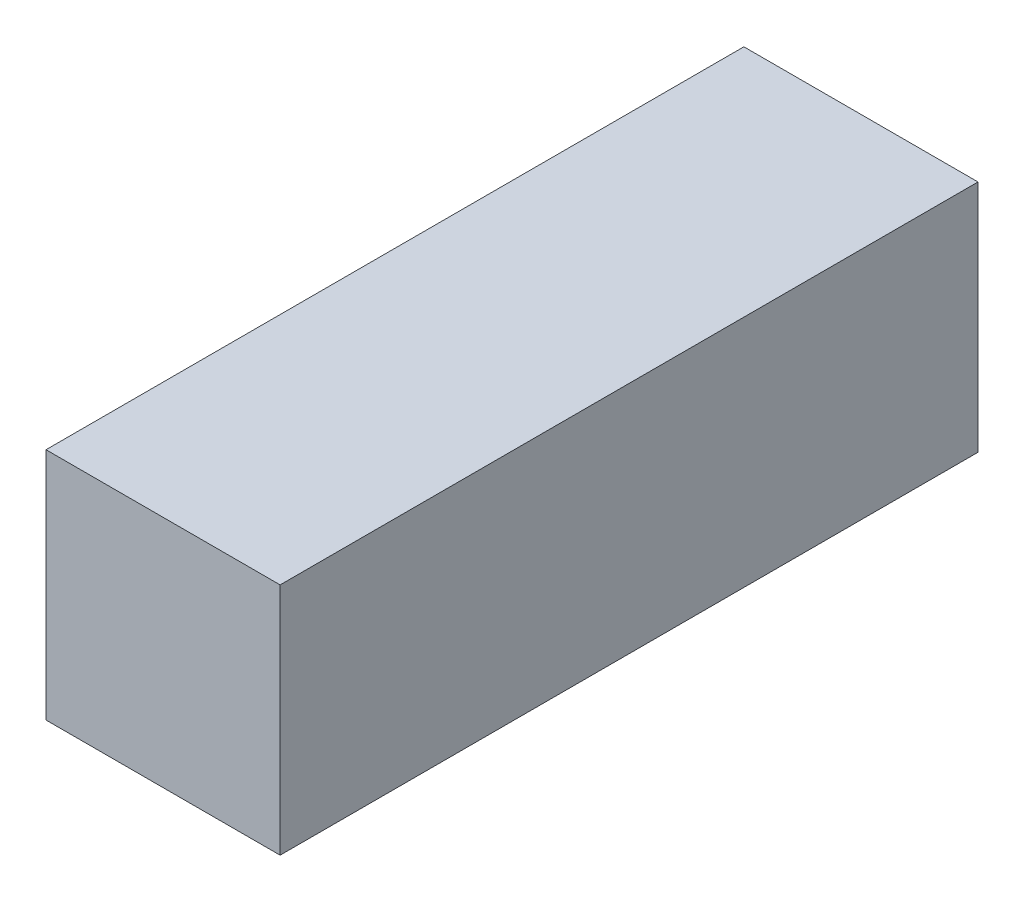
SolidWorks part; units mm, degrees
ref_plane "Front Plane" through (0, 0, 0) normal (0, 0, 1) x (1, 0, 0)
ref_plane "Top Plane" through (0, 0, 0) normal (0, 1, 0) x (1, 0, 0)
ref_plane "Right Plane" through (0, 0, 0) normal (1, 0, 0) x (0, 0, -1)
sketch "Sketch1" plane through (0, 0, 0) normal (0, 0, 1) x (1, 0, 0)
  line L0 (-1333.5, 2628.9) -> (-1333.5, -38.1)
  line L1 (-1295.4, 2590.8) -> (1295.4, 2590.8)
  line L2 (-1295.4, 2590.8) -> (-1295.4, 0)
  line L3 (-1295.4, 0) -> (1295.4, 0)
  line L4 (1295.4, 2590.8) -> (1295.4, 0)
  line L5 (-1295.4, 2590.8) -> (1295.4, 0) construction
  line L6 (-1295.4, 0) -> (1295.4, 2590.8) construction
  line L7 (-1333.5, -38.1) -> (1333.5, -38.1)
  line L8 (1333.5, 2628.9) -> (1333.5, -38.1)
  line L9 (-1333.5, 2628.9) -> (1333.5, 2628.9)
  point P0 (0, 1295.4)
  dimension "D1" = 2590.8
  dimension "D2" = 2590.8
  dimension "D3" = 38.1
extrude "Boss-Extrude1" add sketch "Sketch1" along normal blind 7924.8
sketch "Sketch2" plane through (0, 0, 7924.8) normal (0, 0, 1) x (1, 0, 0)
  line L0 (-1333.5, -38.1) -> (1333.5, -38.1) construction
  line L1 (1333.5, -38.1) -> (1333.5, 2628.9) construction
  line L2 (1333.5, 2628.9) -> (-1333.5, 2628.9) construction
  line L3 (-1333.5, 2628.9) -> (-1333.5, -38.1) construction
  line L4 (-1333.5, -38.1) -> (1333.5, -38.1)
  line L5 (1333.5, -38.1) -> (1333.5, 2628.9)
  line L6 (1333.5, 2628.9) -> (-1333.5, 2628.9)
  line L7 (-1333.5, 2628.9) -> (-1333.5, -38.1)
extrude "Boss-Extrude2" add sketch "Sketch2" along normal blind 25.4
sketch "Sketch3" plane through (0, 0, 7924.8) normal (0, 0, -1) x (-1, 0, 0)
  line L1 (-1295.4, 0) -> (-1155.7, 0)
  line L2 (-1295.4, 0) -> (-1295.4, 88.9)
  line L3 (-1295.4, 88.9) -> (-1155.7, 88.9)
  line L4 (-1155.7, 0) -> (-1155.7, 88.9)
  dimension "D1" = 139.7
  dimension "D2" = 88.9
extrude "Boss-Extrude3" add sketch "Sketch3" along normal blind 4876.8
sketch "Sketch4" plane through (0, 0, 0) normal (0, 1, 0) x (1, 0, 0)
  line L1 (-1276.3768, -7908.9884) -> (-57.1768, -7908.9884)
  line L2 (-1276.3768, -7908.9884) -> (-1276.3768, -6892.9884)
  line L3 (-1276.3768, -6892.9884) -> (-57.1768, -6892.9884)
  line L4 (-57.1768, -7908.9884) -> (-57.1768, -6892.9884)
  dimension "D1" = 1219.2
  dimension "D2" = 1016
extrude "Boss-Extrude4" add sketch "Sketch4" along normal blind 152.4
pattern_linear "LPattern1" count 9 spacing 142.24 along (-1, 0, 0) count 9 spacing 91.44 along (0, 1, 0) of "Boss-Extrude3"
